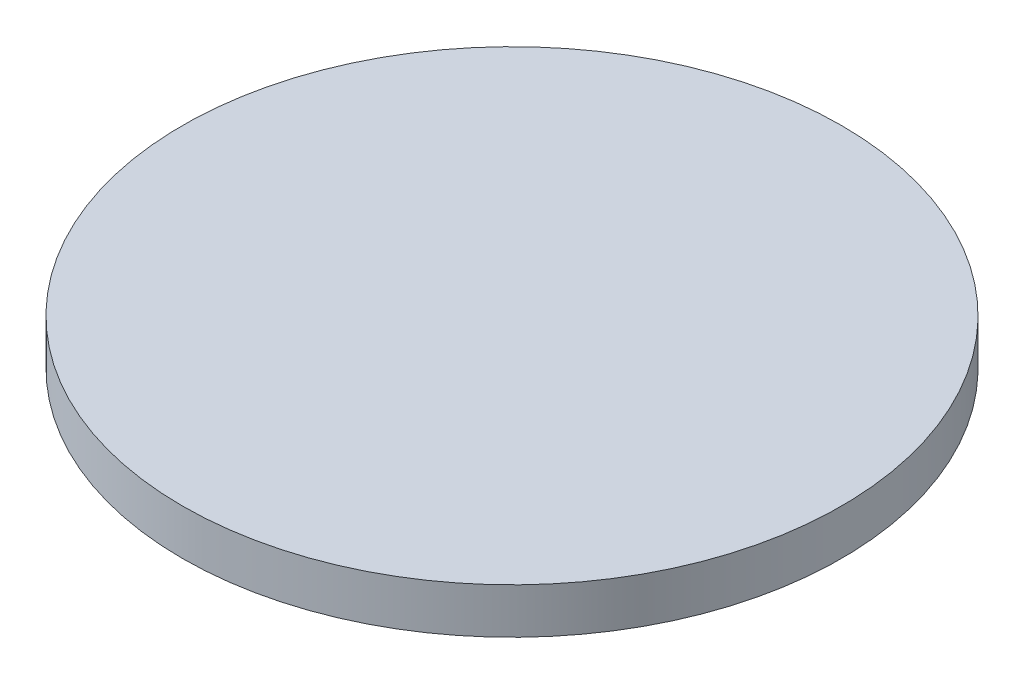
SolidWorks part; units mm, degrees
ref_plane "Front Plane" through (0, 0, 0) normal (0, 0, 1) x (1, 0, 0)
ref_plane "Top Plane" through (0, 0, 0) normal (0, 1, 0) x (1, 0, 0)
ref_plane "Right Plane" through (0, 0, 0) normal (1, 0, 0) x (0, 0, -1)
other "Configuration Table"
sketch "Sketch1" plane through (0, 0, 0) normal (0, 1, 0) x (1, 0, 0)
  circle A0 centre (350, 280) radius 145
extrude "PRESS_PZP400_ust_plaka_D290" add sketch "Sketch1" along normal blind 20 from offset 1000 separate body
